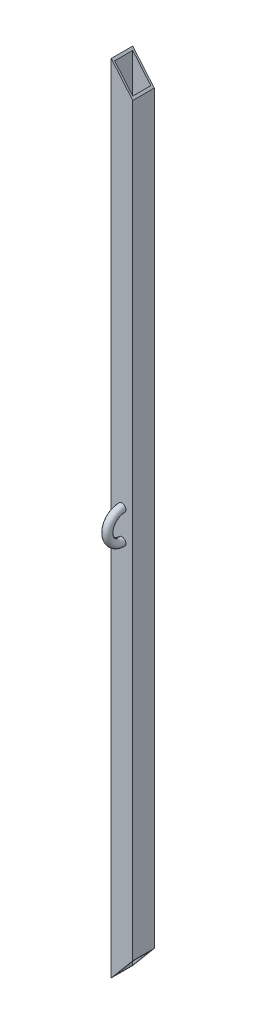
SolidWorks part; units mm, degrees
material "Alloy Steel"
ref_plane "Front Plane" through (0, 0, 0) normal (0, 0, 1) x (1, 0, 0)
ref_plane "Top Plane" through (0, 0, 0) normal (0, 1, 0) x (1, 0, 0)
ref_plane "Right Plane" through (0, 0, 0) normal (1, 0, 0) x (0, 0, -1)
sketch "Sketch2" plane through (0, 0, 0) normal (0, 1, 0) x (1, 0, 0)
  line L0 (-13.335, 13.335) -> (13.335, 13.335)
  line L1 (-15.875, 15.875) -> (15.875, 15.875)
  line L2 (-15.875, 15.875) -> (-15.875, -15.875)
  line L3 (-15.875, -15.875) -> (15.875, -15.875)
  line L4 (15.875, 15.875) -> (15.875, -15.875)
  line L5 (-15.875, 15.875) -> (15.875, -15.875) construction
  line L6 (-15.875, -15.875) -> (15.875, 15.875) construction
  line L7 (13.335, 13.335) -> (13.335, -13.335)
  line L8 (-13.335, -13.335) -> (13.335, -13.335)
  line L9 (-13.335, 13.335) -> (-13.335, -13.335)
  point P0 (0, 0)
  dimension "D1" = 31.75
  dimension "D2" = 31.75
  dimension "D3" = 2.54
extrude "Boss-Extrude1" add sketch "Sketch2" along normal blind 1174.75
sketch "Sketch4" plane through (0, 0, 15.875) normal (0, 0, 1) x (1, 0, 0)
  line L0 (15.875, 0) -> (15.875, 37.8382)
  line L3 (-15.875, 0) -> (15.875, 0)
  line L4 (15.875, 1174.75) -> (15.875, 1136.9118)
  line L6 (-15.875, 1174.75) -> (15.875, 1174.75)
  line L7 (-15.875, 1174.75) -> (15.875, 1136.9118)
  line L8 (-15.875, 0) -> (15.875, 37.8382)
  dimension "D1" = 50
  dimension "D2" = 50
  dimension "D3" = 37.8382
  dimension "D4" = 37.8382
extrude "Cut-Extrude1" cut sketch "Sketch4" against normal through all
ref_plane "Plane1" through (0, 0, 0) normal (1, 0, 0) x (0, 0, -1)
sketch "Sketch7" plane through (0, 0, 0) normal (1, 0, 0) x (0, 0, -1)
  line L0 (42.789, 587.375) -> (-130.1942, 587.375) construction
  line L1 (-15.875, 1174.75) -> (-15.875, 0) construction
  arc A2 (-15.875, 608.965) -> (-15.875, 565.785) centre (-15.875, 587.375) ccw
  point P4 (-15.875, 587.375)
sketch "Sketch8" plane through (0, 0, 15.875) normal (0, 0, 1) x (1, 0, 0)
  line L0 (0, 1174.75) -> (0, 0) construction
  line L1 (0, 565.785) -> (0, 608.965) construction
  circle A0 centre (0, 608.965) radius 5.842
  dimension "D1" = 11.684
sweep "Sweep2" add profiles "Sketch8" path "Sketch7"
